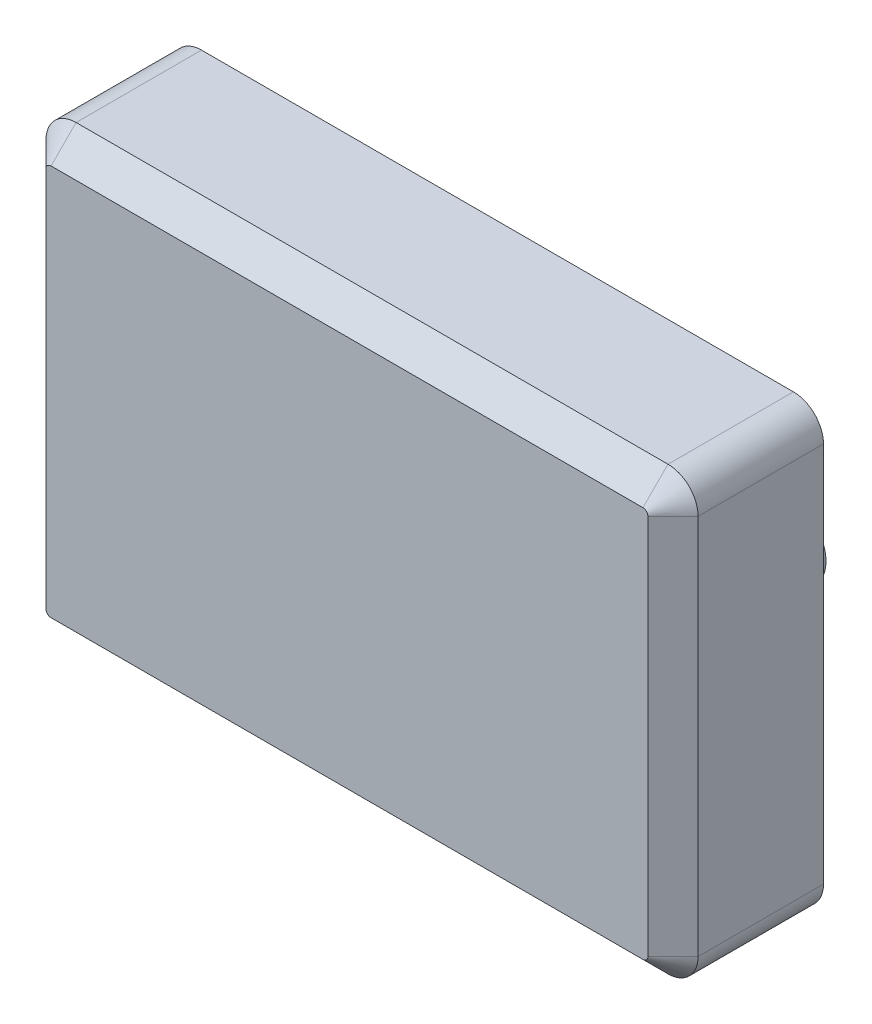
SolidWorks part; units mm, degrees
ref_plane "前视基准面" through (0, 0, 0) normal (0, 0, 1) x (1, 0, 0)
ref_plane "上视基准面" through (0, 0, 0) normal (0, 1, 0) x (1, 0, 0)
ref_plane "右视基准面" through (0, 0, 0) normal (1, 0, 0) x (0, 0, -1)
other "Configuration Table"
sketch "草图4" plane through (0, 0, 0) normal (0, 0, 1) x (1, 0, 0)
  line L0 (-5.9, -4.4) -> (5.9, -4.4)
  line L1 (6.5, -3.8) -> (6.5, 3.8)
  line L2 (5.9, 4.4) -> (-5.9, 4.4)
  line L3 (-6.5, 3.8) -> (-6.5, -3.8)
  arc A0 (5.9, -4.4) -> (6.5, -3.8) centre (5.9, -3.8) ccw
  arc A1 (6.5, 3.8) -> (5.9, 4.4) centre (5.9, 3.8) ccw
  arc A2 (-5.9, 4.4) -> (-6.5, 3.8) centre (-5.9, 3.8) ccw
  arc A3 (-6.5, -3.8) -> (-5.9, -4.4) centre (-5.9, -3.8) ccw
extrude "Cover_feature11_13x8.8_R0.6_H1.5" add sketch "草图4" along normal blind 3
sketch "草图5" plane through (0, 0, 0) normal (0, 0, 1) x (1, 0, 0)
  circle A0 centre (-4, 0) radius 0.75
  circle A1 centre (4, 0) radius 0.75
extrude "Locating_pins_D1.5_pitch8_length1.8" add sketch "草图5" against normal blind 1.8
chamfer "倒角1" distance 0.5 angle 45 8 edges at (0, 4.4, 3) (-6.3243, 4.2243, 3) (6.3243, 4.2243, 3) (-6.5, 0, 3) (6.5, 0, 3) (-6.3243, -4.2243, 3) (6.3243, -4.2243, 3) (0, -4.4, 3)
